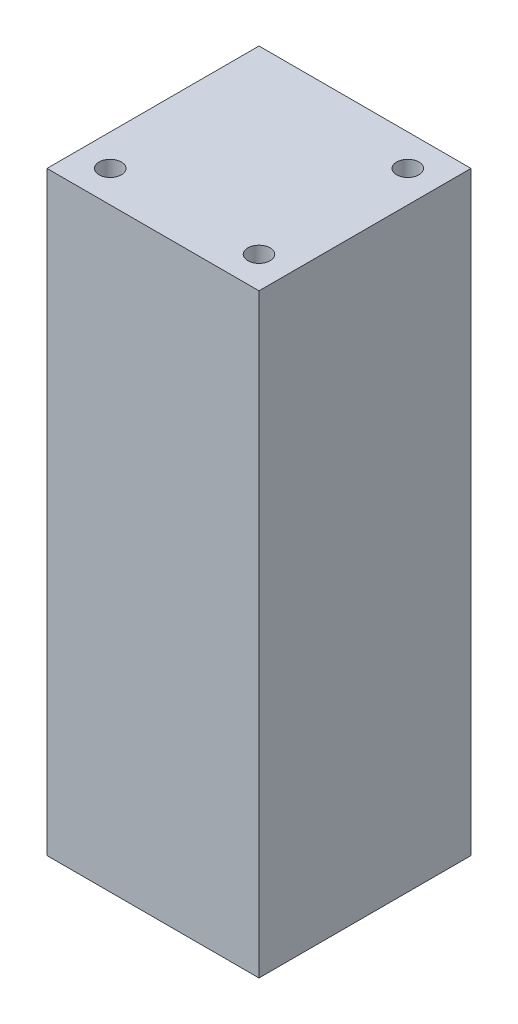
SolidWorks part; units mm, degrees
material "Oak"
ref_plane "Front Plane" through (0, 0, 0) normal (0, 0, 1) x (1, 0, 0)
ref_plane "Top Plane" through (0, 0, 0) normal (0, 1, 0) x (1, 0, 0)
ref_plane "Right Plane" through (0, 0, 0) normal (1, 0, 0) x (0, 0, -1)
sketch "Sketch1" plane through (0, 0, 0) normal (0, 1, 0) x (1, 0, 0)
  line L1 (-14.25, 14.25) -> (14.25, 14.25)
  line L2 (-14.25, 14.25) -> (-14.25, -14.25)
  line L3 (-14.25, -14.25) -> (14.25, -14.25)
  line L4 (14.25, 14.25) -> (14.25, -14.25)
  line L5 (-14.25, 14.25) -> (14.25, -14.25) construction
  line L6 (-14.25, -14.25) -> (14.25, 14.25) construction
  point P0 (0, 0)
  dimension "D1" = 28.5
extrude "Boss-Extrude1" add sketch "Sketch1" along normal blind 80
sketch "Sketch2" plane through (0, 80, 0) normal (0, 1, 0) x (1, 0, 0)
  circle A0 centre (10, 10) radius 1.5
  circle A1 centre (10, -10) radius 1.5
  circle A2 centre (-10, -10) radius 1.5
  dimension "D1" = 3
  dimension "D2" = 3
  dimension "D3" = 3
  dimension "D4" = 20
  dimension "D5" = 20
extrude "Cut-Extrude1" cut sketch "Sketch2" against normal blind 12
